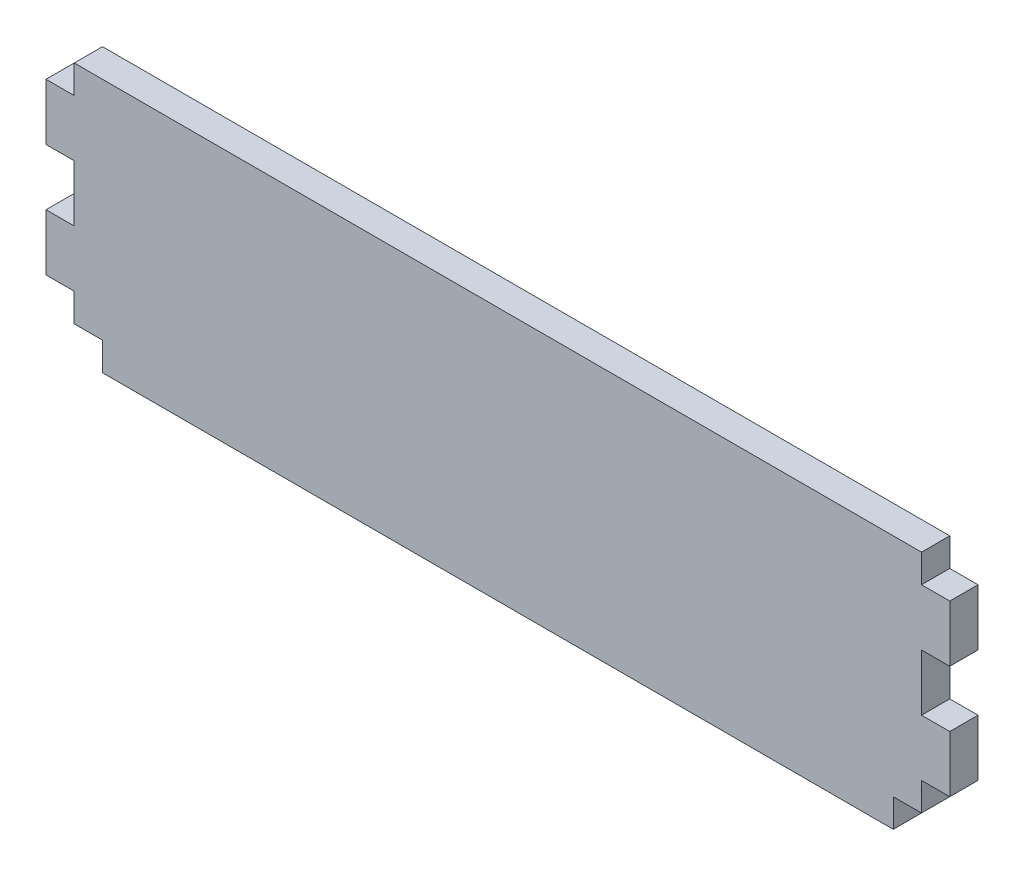
SolidWorks part; units mm, degrees
ref_plane "Plan de face" through (0, 0, 0) normal (0, 0, 1) x (1, 0, 0)
ref_plane "Plan de dessus" through (0, 0, 0) normal (0, 1, 0) x (1, 0, 0)
ref_plane "Plan de droite" through (0, 0, 0) normal (1, 0, 0) x (0, 0, -1)
sketch "Esquisse1" plane through (0, 0, 0) normal (0, 0, 1) x (1, 0, 0)
  line L0 (85.505, -34.2237) -> (85.505, -29.2237)
  line L5 (-69.495, -34.2237) -> (-64.495, -34.2237)
  line L6 (-69.495, -34.2237) -> (-69.495, -44.2237)
  line L7 (-69.495, -44.2237) -> (-64.495, -44.2237)
  line L9 (-69.495, -54.2237) -> (-64.495, -54.2237)
  line L10 (-69.495, -54.2237) -> (-69.495, -64.2237)
  line L11 (-69.495, -64.2237) -> (-64.495, -64.2237)
  line L13 (90.505, -34.2237) -> (85.505, -34.2237)
  line L14 (90.505, -34.2237) -> (90.505, -44.2237)
  line L15 (90.505, -44.2237) -> (85.505, -44.2237)
  line L17 (90.505, -54.2237) -> (85.505, -54.2237)
  line L18 (90.505, -54.2237) -> (90.505, -64.2237)
  line L19 (90.505, -64.2237) -> (85.505, -64.2237)
  line L20 (85.505, -64.2237) -> (85.505, -69.2237)
  line L21 (85.505, -54.2237) -> (85.505, -44.2237)
  line L22 (-64.495, -34.2237) -> (-64.495, -29.2237)
  line L23 (-64.495, -29.2237) -> (85.505, -29.2237)
  line L24 (-64.495, -54.2237) -> (-64.495, -44.2237)
  line L25 (-64.495, -64.2237) -> (-64.495, -69.2237)
  line L26 (85.505, -69.2237) -> (-64.495, -69.2237)
  dimension "D4" = 10
  dimension "D5" = 10
  dimension "D6" = 10
  dimension "D14" = 10
  dimension "D15" = 10
  dimension "D16" = 10
extrude "Boss.-Extru.1" add sketch "Esquisse1" along normal blind 5
sketch "Esquisse2" plane through (0, 0, 5) normal (0, 0, 1) x (1, 0, 0)
  line L0 (-64.495, -69.2237) -> (85.505, -69.2237) construction
  line L1 (-59.495, -69.2237) -> (80.505, -69.2237)
  line L2 (-59.495, -69.2237) -> (-59.495, -74.2237)
  line L3 (-59.495, -74.2237) -> (80.505, -74.2237)
  line L4 (80.505, -69.2237) -> (80.505, -74.2237)
  line L5 (-64.495, -64.2237) -> (-64.495, -69.2237) construction
  dimension "D1" = 5
  dimension "D2" = 5
  dimension "D3" = 140
extrude "Boss.-Extru.2" add sketch "Esquisse2" against normal blind 5
